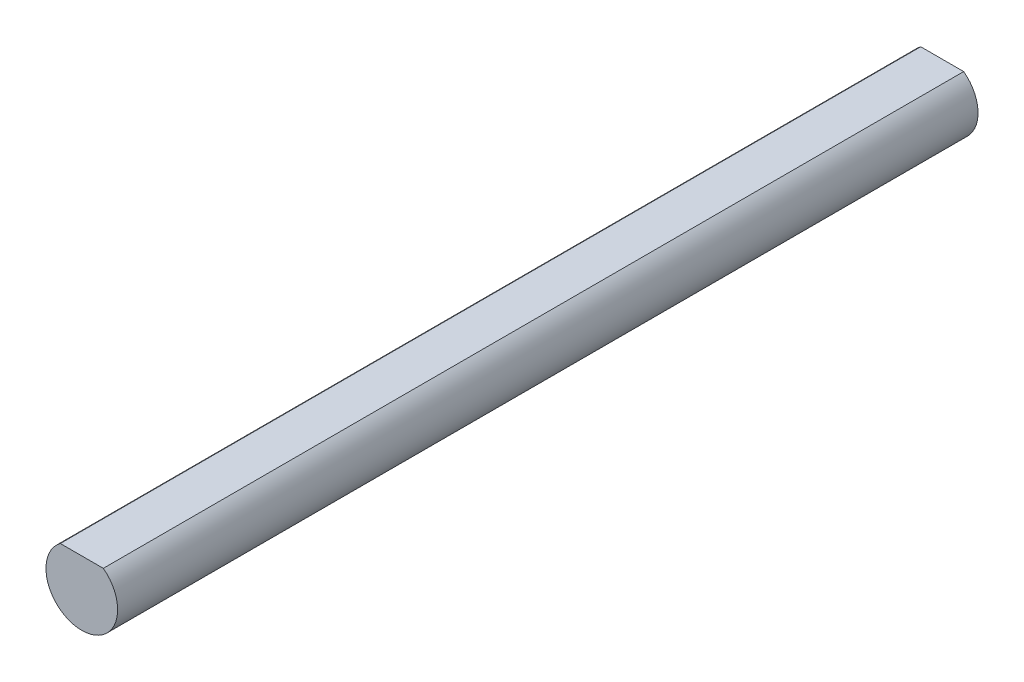
SolidWorks part; units mm, degrees
material "Acier allié inoxydable"
ref_plane "Plan de face" through (0, 0, 0) normal (0, 0, 1) x (1, 0, 0)
ref_plane "Plan de dessus" through (0, 0, 0) normal (0, 1, 0) x (1, 0, 0)
ref_plane "Plan de droite" through (0, 0, 0) normal (1, 0, 0) x (0, 0, -1)
sketch "Esquisse2" plane through (0, 0, 0) normal (0, 0, 1) x (1, 0, 0)
  line L0 (-1.905, 2.54) -> (1.905, 2.54)
  arc A0 (-1.905, 2.54) -> (1.905, 2.54) centre (0, 0) ccw
  point P4 (0, -3.175)
  dimension "D1" = 3.175
  dimension "D2" = 5.715
  dimension "D3" = 2.54
extrude "Boss.-Extru.1" add sketch "Esquisse2" along normal blind 76.2 contours A0 L0
